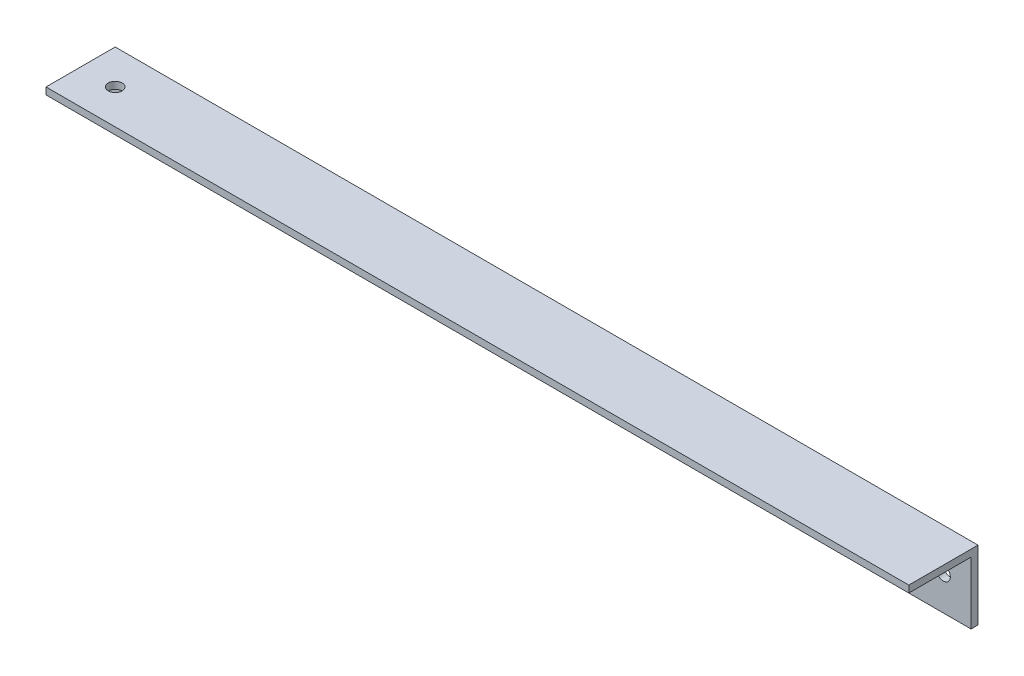
SolidWorks part; units mm, degrees
ref_plane "Plan de face" through (0, 0, 0) normal (0, 0, 1) x (1, 0, 0)
ref_plane "Plan de dessus" through (0, 0, 0) normal (0, 1, 0) x (1, 0, 0)
ref_plane "Plan de droite" through (0, 0, 0) normal (1, 0, 0) x (0, 0, -1)
sketch "Esquisse1" plane through (0, 0, 0) normal (0, 0, 1) x (1, 0, 0)
  line L1 (-79.9291, 17.0447) -> (107.0709, 17.0447)
  line L2 (-79.9291, 17.0447) -> (-79.9291, 2.0447)
  line L3 (-79.9291, 2.0447) -> (107.0709, 2.0447)
  line L4 (107.0709, 17.0447) -> (107.0709, 2.0447)
  circle A1 centre (101.0709, 9.5447) radius 1.5
  circle A2 centre (-72.4291, 8.0447) radius 1.5
  circle A3 centre (-31.4291, 8.0447) radius 1.5
  circle A4 centre (68.5709, 8.0447) radius 1.5
  dimension "D3" = 7.5
  dimension "D5" = 6
  dimension "D8" = 38.5
  dimension "D1" = 187
  dimension "D2" = 15
  dimension "D6" = 7.5
  dimension "D9" = 138.5
  dimension "D10" = 6
  dimension "D11" = 6
  dimension "D12" = 6
extrude "Extrusion1" add sketch "Esquisse1" along normal blind 1.5
sketch "Esquisse3" plane through (0, 0, 1.5) normal (0, 0, 1) x (1, 0, 0)
  line L0 (-79.9291, 17.0447) -> (-79.9291, 2.0447) construction
  line L1 (107.0709, 17.0447) -> (-79.9291, 17.0447)
  line L2 (107.0709, 17.0447) -> (107.0709, 15.5447)
  line L3 (107.0709, 15.5447) -> (-79.9291, 15.5447)
  line L4 (-79.9291, 17.0447) -> (-79.9291, 15.5447)
  dimension "D1" = 1.5
extrude "Extrusion3" add sketch "Esquisse3" along normal blind 13.5
sketch "Esquisse4" plane through (0, 15.5447, 0) normal (0, -1, 0) x (1, 0, 0)
  line L0 (-79.9291, 15) -> (107.0709, 15) construction
  line L1 (-79.9291, 15) -> (-79.9291, 1.5) construction
  circle A0 centre (-72.4291, 7.5) radius 1.5
  dimension "D1" = 7.5
  dimension "D2" = 7.5
extrude "Extrusion4" cut sketch "Esquisse4" against normal blind 10
